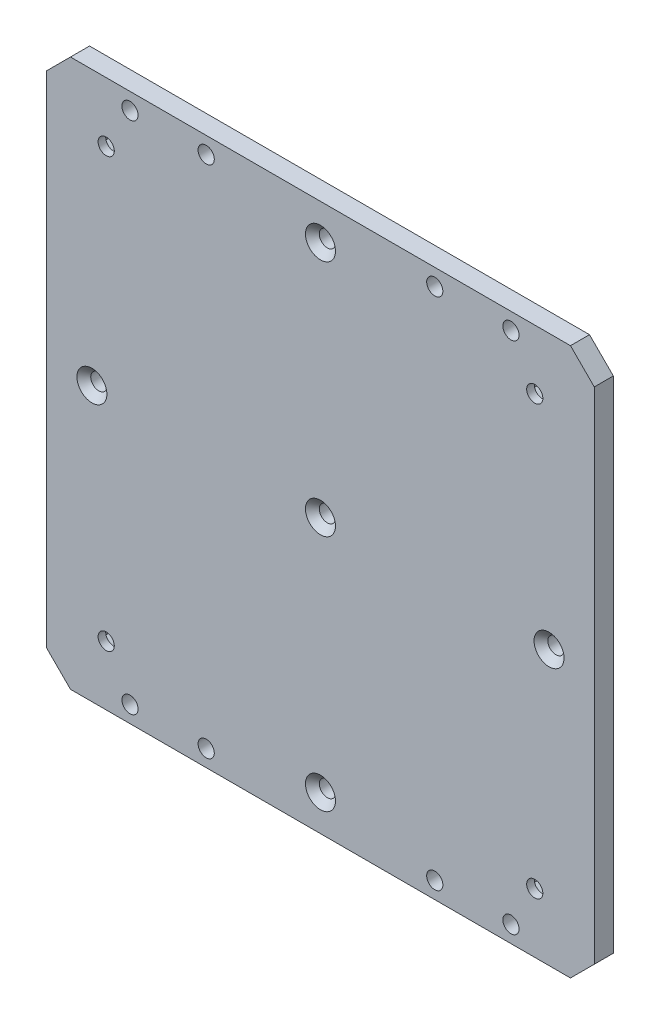
SolidWorks part; units mm, degrees
ref_plane "1" through (0, 0, 0) normal (0, 0, 1) x (1, 0, 0)
ref_plane "2" through (0, 0, 0) normal (0, 1, 0) x (1, 0, 0)
ref_plane "3" through (0, 0, 0) normal (1, 0, 0) x (0, 0, -1)
ref_plane "Front Plane" through (0, 0, 0) normal (0, -1, 0) x (1, 0, 0)
ref_plane "Right Plane" through (0, 0, 0) normal (1, 0, 0) x (0, 1, 0)
ref_plane "Top Plane" through (0, 0, 0) normal (0, 0, 1) x (1, 0, 0)
ref_plane "Plane1" through (0, 0, 1.6) normal (0, 0, 1) x (1, 0, 0)
sketch "Sketch1" plane through (0, 0, 0) normal (0, 0, 1) x (1, 0, 0)
  line L0 (-57.5, 57.5) -> (57.5, 57.5) construction
  line L1 (-57.5, 57.5) -> (-57.5, -57.5) construction
  line L2 (57.5, 57.5) -> (57.5, -57.5) construction
  line L3 (-57.5, -57.5) -> (57.5, -57.5) construction
  line L4 (0, 57.5) -> (0, 66.5129) construction
  line L5 (57.5, 0) -> (80.0122, 0) construction
  line L14 (-45, 45) -> (45, 45) construction
  line L15 (-45, 45) -> (-45, -45) construction
  line L16 (45, 45) -> (45, -45) construction
  line L17 (-45, -45) -> (45, -45) construction
  line L18 (0, 45) -> (0, 40.4761) construction
  line L19 (45, 0) -> (34.1739, 0) construction
  circle A0 centre (45, 45) radius 1.5 construction
  circle A1 centre (-45, 45) radius 1.5 construction
  circle A2 centre (-45, -45) radius 1.5 construction
  circle A3 centre (45, -45) radius 1.5 construction
  dimension "D4" = 3
  dimension "D1" = 115
  dimension "D2" = 115
  dimension "D3" = 90
  dimension "D5" = 90
sketch "Sketch2" plane through (0, 0, 0) normal (0, 0, 1) x (1, 0, 0)
  line L8 (0, 57.5) -> (0, 0)
  line L9 (0, 0) -> (57.5, 0)
  line L10 (57.5, 0) -> (57.5, 57.5)
  line L14 (57.5, 57.5) -> (0, 57.5)
  line L15 (-57.5, 57.5) -> (57.5, 57.5) construction
  line L16 (57.5, 57.5) -> (57.5, -57.5) construction
extrude "Boss-Extrude1" add sketch "Sketch2" along normal blind 4
sketch "Sketch12" plane through (0, 0, 0) normal (0, 0, 1) x (1, 0, 0)
  line L1 (45, 41.7668) -> (47.8, 43.3834)
  line L2 (47.8, 43.3834) -> (47.8, 46.6166)
  line L3 (47.8, 46.6166) -> (45, 48.2332)
  line L4 (45, 48.2332) -> (42.2, 46.6166)
  line L5 (42.2, 46.6166) -> (42.2, 43.3834)
  line L6 (42.2, 43.3834) -> (45, 41.7668)
  circle A0 centre (45, 45) radius 2.8 construction
  circle A1 centre (45, 45) radius 1.5 construction
  dimension "D1" = 5.6
extrude "Cut-Extrude4" cut sketch "Sketch12" along normal blind 2.4
hole_wizard "M3 Clearance Hole1" positions "Sketch3" profile "Sketch5" hole size "M3" standard "ANSI Metric" end condition through all
sketch "Sketch3" plane through (0, 0, 4) normal (0, 0, 1) x (1, 0, 0)
  circle A0 centre (45, 45) radius 1.5 construction
  circle A1 centre (-45, 45) radius 1.5 construction
  circle A2 centre (-45, -45) radius 1.5 construction
  circle A3 centre (45, -45) radius 1.5 construction
  point P0 (45, 45)
  point P2 (-45, 45)
  point P4 (-45, -45)
  point P6 (45, -45)
sketch "Sketch5" plane through (45, 45, 4) normal (1, 0, 0) x (0, -1, 0)
  line L0 (0, 0) -> (0, 4)
  line L1 (0, 4) -> (1.7, 4)
  line L2 (1.7, 4) -> (1.7, 0)
  line L5 (1.7, 0) -> (0, 0)
  line L11 (0, -6.35) -> (0, 107.95) construction
  dimension "Thru Hole Dia." = 3.4
  dimension "Thru Hole Depth" = 4
sketch "Sketch6" plane through (0, 0, 0) normal (0, 0, 1) x (1, 0, 0)
  line L0 (0, 50) -> (0, 0) construction
  line L1 (0, 0) -> (48, 0) construction
  circle A3 centre (0, 50) radius 1.5
  circle A4 centre (0, 0) radius 1.5
  circle A5 centre (48, 0) radius 1.5
  dimension "D1" = 3
  dimension "D2" = 50
  dimension "D3" = 48
hole_wizard "CSK for M3 Flat Head Machine Screw1" positions "Sketch9" profile "Sketch10" countersink size "M3" standard "ANSI Metric" end condition through all
sketch "Sketch9" plane through (0, 0, 4) normal (0, 0, 1) x (1, 0, 0)
  circle A3 centre (0, 50) radius 1.5 construction
  circle A4 centre (0, 0) radius 1.5 construction
  circle A5 centre (48, 0) radius 1.5 construction
  point P0 (0, 50)
  point P2 (0, 0)
  point P4 (48, 0)
sketch "Sketch10" plane through (0, 50, 4) normal (1, 0, 0) x (0, -1, 0)
  line L0 (0, 0) -> (0, 4)
  line L1 (0, 4) -> (1.7, 4)
  line L2 (1.7, 4) -> (1.7, 1.45)
  line L3 (1.7, 1.45) -> (3.15, 0)
  line L5 (3.15, 0) -> (0, 0)
  line L6 (-1.7, 1.45) -> (-3.15, 0) construction
  line L11 (0, -6.35) -> (0, 107.95) construction
  dimension "Thru Hole Dia." = 3.4
  dimension "Thru Hole Depth" = 4
  dimension "Near C'Sink Dia." = 6.3
  dimension "Near C'Sink Angle" = 90
sketch "Sketch11" [suppressed] plane through (0, 0, 0) normal (0, 0, 1) x (1, 0, 0)
  line L0 (12, 38) -> (12, 18)
  line L1 (12, 38) -> (29.5, 38)
  line L2 (12, 18) -> (29.5, 18)
  line L3 (29.5, 38) -> (29.5, 18)
  line L4 (12, 28) -> (8.7244, 28) construction
  line L5 (0, -31.3359) -> (0, 31.3359) construction
  dimension "D1" = 28
  dimension "D2" = 20
  dimension "D3" = 12
  dimension "D4" = 29.5
extrude "Cut-Extrude3" [suppressed] cut sketch "Sketch11" along normal through all
fillet "Fillet1" [suppressed] radius 2
sketch "Sketch15" plane through (0, 0, 0) normal (0, 0, 1) x (1, 0, 0)
  line L0 (0, 54) -> (40, 54) construction
  line L1 (40, 54) -> (48, 54) construction
  line L2 (48, 54) -> (48, 46) construction
  line L3 (48, 46) -> (48, 0) construction
  line L4 (48, 0) -> (0, 0) construction
  line L5 (0, 0) -> (0, 54) construction
  circle A0 centre (40, 54) radius 1.5 construction
  circle A2 centre (24, 54) radius 1.5 construction
  dimension "D4" = 3
  dimension "D5" = 16
  dimension "D1" = 54
  dimension "D2" = 48
  dimension "D3" = 40
hole_wizard "CSK for M3 Flat Head Machine Screw2" positions "Sketch13" profile "Sketch14" countersink size "M3" standard "ANSI Metric" end condition through all
sketch "Sketch13" plane through (0, 0, 0) normal (0, 0, -1) x (-1, 0, 0)
  circle A0 centre (-24, 54) radius 1.5 construction
  circle A1 centre (-40, 54) radius 1.5 construction
  point P0 (-24, 54)
  point P2 (-40, 54)
sketch "Sketch14" plane through (24, 54, 0) normal (1, 0, 0) x (0, 1, 0)
  line L0 (0, 0) -> (0, 4)
  line L1 (0, 4) -> (1.7, 4)
  line L2 (1.7, 4) -> (1.7, 1.45)
  line L3 (1.7, 1.45) -> (3.15, 0)
  line L5 (3.15, 0) -> (0, 0)
  line L6 (-1.7, 1.45) -> (-3.15, 0) construction
  line L11 (0, -6.35) -> (0, 107.95) construction
  dimension "Thru Hole Dia." = 3.4
  dimension "Thru Hole Depth" = 4
  dimension "Near C'Sink Dia." = 6.3
  dimension "Near C'Sink Angle" = 90
chamfer "Chamfer1" distance 5 angle 45 1 edges at (57.5, 57.5, 2)
mirror "Mirror1" about plane through (0, 0, 0) normal (0, -1, 0) of bodies 110 102
mirror "Mirror2" about plane through (0, 0, 0) normal (1, 0, 0) of bodies 103
